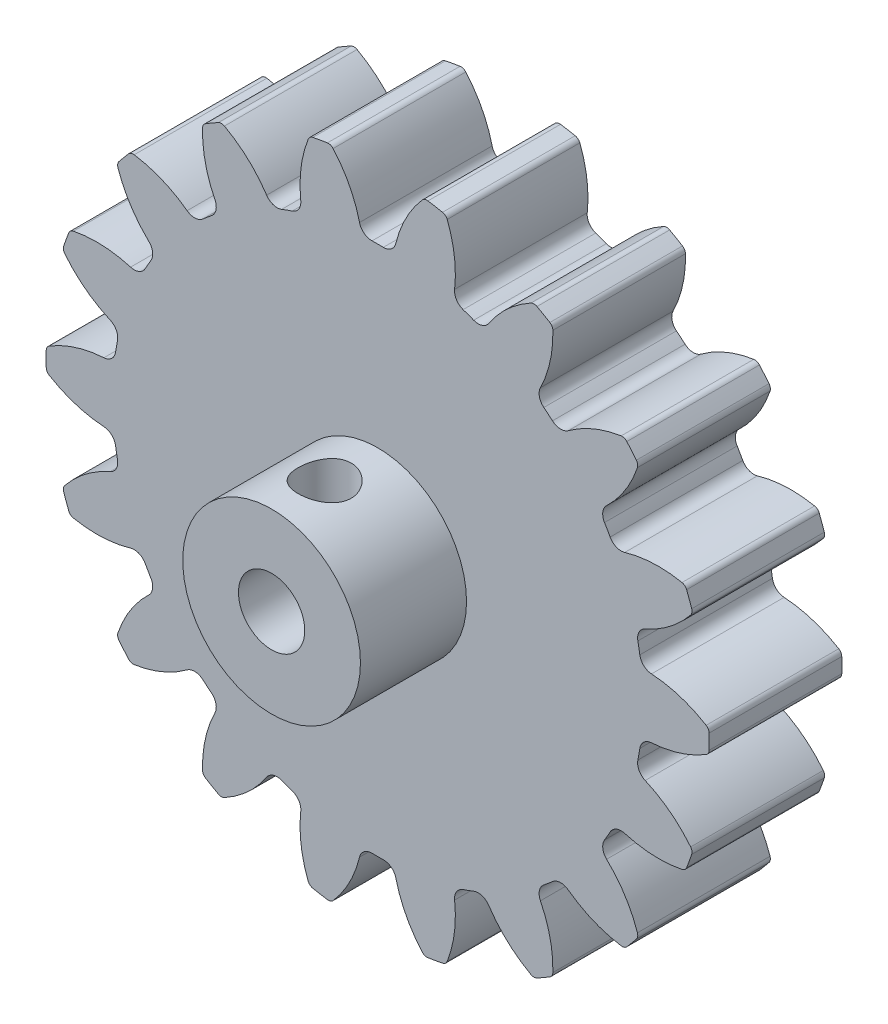
SolidWorks part; units mm, degrees
ref_plane "Front Plane" through (0, 0, 0) normal (0, 0, 1) x (1, 0, 0)
ref_plane "Top Plane" through (0, 0, 0) normal (0, 1, 0) x (1, 0, 0)
ref_plane "Right Plane" through (0, 0, 0) normal (1, 0, 0) x (0, 0, -1)
sketch "Sketch1" plane through (0, 0, 0) normal (0, 0, 1) x (1, 0, 0)
  line L0 (-9, 0) -> (9, 0) construction
  line L1 (0, 0) -> (0, 7.5) construction
  circle A0 centre (0, 0) radius 25 construction
  circle A1 centre (0, 0) radius 22.5 construction
  circle A2 centre (0, 0) radius 20 construction
  point P9 (2.5, 0)
  dimension "D1" = 40
  dimension "OD" = 50
  dimension "Pitch Dia." = 45
  dimension "Number of Teeth" = 18
  dimension "Module" = 2.5
sketch "Sketch4" plane through (0, 0, 0) normal (1, 0, 0) x (0, 0, -1)
  line L0 (-10, 25) -> (-10, 0)
  line L1 (0, 0) -> (-10, 0)
  line L2 (0, 0) -> (0, 25)
  line L3 (-10, 25) -> (0, 25)
  line L6 (0, 25) -> (0, -25) construction
  dimension "D1" = 25
  dimension "D2" = 10
revolve "Revolve1" add sketch "Sketch4" angle 360 about L1
sketch "Sketch7" plane through (0, 0, 10) normal (0, 0, 1) x (1, 0, 0)
  line L0 (0, 0) -> (0, 25) construction
  line L1 (1.961, 22.4144) -> (3.078, 24.8098) construction
  line L3 (4.3412, 24.6202) -> (3.9071, 22.1582) construction
  line L4 (3.9071, 22.1582) -> (3.473, 19.6962) construction
  line L5 (0, 0) -> (3.473, 19.6962) construction
  line L6 (1.961, 22.4144) -> (0, 0) construction
  line L7 (1.961, 22.4144) -> (2.1789, 24.9049) construction
  line L8 (1.961, 22.4144) -> (0, 0) construction
  circle A0 centre (0, 0) radius 25 construction
  circle A2 centre (0, 0) radius 20 construction
  arc A3 (-1.961, 22.4144) -> (1.961, 22.4144) centre (0, 0) cw construction
  circle A4 centre (0, 0) radius 22.5 construction
  arc A5 (5.1423, 24.4654) -> (3.5355, 24.7487) centre (0, 0) ccw construction
  arc A6 (1.961, 22.4144) -> (5.8234, 21.7333) centre (0, 0) cw construction
  arc A7 (-3.5355, 24.7487) -> (3.5355, 24.7487) centre (0, 0) cw
  arc A8 (1.2199, 19.9628) -> (3.5355, 24.7487) centre (10.1178, 18.6108) cw
  arc A9 (-1.2199, 19.9628) -> (-3.5355, 24.7487) centre (-10.1178, 18.6108) ccw
  arc A10 (1.2199, 19.9628) -> (-1.2199, 19.9628) centre (0, 0) ccw
  point P26 (-1.2199, 19.9628)
  point P29 (1.2199, 19.9628)
  dimension "D5" = 9
  dimension "D3" = 20
  dimension "D1" = 7.854
  dimension "D2" = 3.927
extrude "Cut-Extrude2" cut sketch "Sketch7" against normal through all
fillet "Fillet3" radius 0.95 2 edges at (1.2199, 19.9628, 5) (-1.2199, 19.9628, 5)
fillet "Fillet4" radius 0.475 2 edges at (3.5355, 24.7487, 5) (-3.5355, 24.7487, 5)
pattern_circular "CirPattern1" count 18 over 360 about axis through (0, 0, 0) along (0, 0, 1) of "Cut-Extrude2", "Fillet3", "Fillet4"
sketch "Esquisse1" plane through (0, 0, 10) normal (0, 0, 1) x (1, 0, 0)
  circle A0 centre (0, 0) radius 2.5
  circle A1 centre (0, 0) radius 6.7
  dimension "D1" = 5
  dimension "D2" = 4.2
extrude "Boss.-Extru.1" add sketch "Esquisse1" along normal blind 8
hole_wizard "Diamètre du perçage Ø4.0 (4)1" positions "Esquisse2" profile "Esquisse4" hole size "Ø4.0" standard "Ansi Metric"
sketch "Esquisse2" plane through (0, 0, 0) normal (0, 1, 0) x (1, 0, 0)
  line L0 (0, -10) -> (0, -18) construction
  line L1 (-6.7, -10) -> (6.7, -10) construction
  line L2 (-6.7, -18) -> (6.7, -18) construction
  point P0 (0, -14)
sketch "Esquisse4" plane through (0, 0, 14) normal (1, 0, 0) x (0, 0, -1)
  line L0 (0, 0) -> (0, 24.7167)
  line L1 (0, 24.7167) -> (2, 24.7167)
  line L2 (2, 24.7167) -> (2, 0)
  line L5 (2, 0) -> (0, 0)
  line L11 (0, -6.35) -> (0, 107.95) construction
  dimension "Diamètre du perçage jusqu'au prochain" = 4
  dimension "Profondeur du perçage jusqu'au prochain" = 24.7167
sketch "Esquisse5" plane through (0, 0, 10) normal (0, 0, 1) x (1, 0, 0)
  circle A0 centre (0, 0) radius 2.5
  circle A1 centre (0, 0) radius 2.5 construction
extrude "Enlèv. mat.-Extru.1" cut sketch "Esquisse5" against normal through all
equation "\"D1@CirPattern1\"=\"Nb. Dents\""
equation "\"D1@Sketch7\"= pi * ( \"PitchDiametre\" / \"Nb. Dents\" )"
equation "\"D2@Sketch7\"=\"D1@Sketch7\"/2"
equation "\"D1@Fillet3\"=.38mm * \"Mod\""
equation "\"D1@Fillet4\"=\"D1@Fillet3\"/2"
equation "\"D5@Sketch7\"=\"PitchDiametre\"/5"
equation "\"Mod\"= 2.5"
equation "\"Nb. Dents\"= 18"
equation "\"PitchDiametre\"= \"Mod\" * \"Nb. Dents\""
equation "\"OutSideDiameter\"= \"PitchDiametre\" + ( 2 * \"Mod\" )"
equation "\"D1@Sketch4\"=\"OutSideDiameter\"/2"
equation "\"E\"= 10"
equation "\"D2@Sketch4\"=\"E\""
equation "\"PressureAngle\"= 20"
equation "\"D3@Sketch7\"=\"PressureAngle\""
equation "\"FootDiametre\"= \"PitchDiametre\" - ( 2 * \"Mod\" )"
